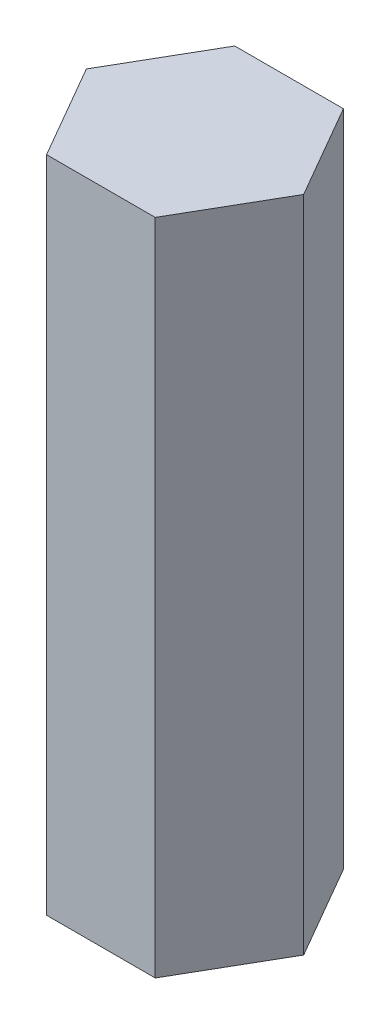
SolidWorks part; units mm, degrees
ref_plane "Plan de face" through (0, 0, 0) normal (0, 0, 1) x (1, 0, 0)
ref_plane "Plan de dessus" through (0, 0, 0) normal (0, 1, 0) x (1, 0, 0)
ref_plane "Plan de droite" through (0, 0, 0) normal (1, 0, 0) x (0, 0, -1)
sketch "Esquisse1" plane through (0, 0, 0) normal (0, 1, 0) x (1, 0, 0)
  line L1 (0, 10) -> (-5.7735, 20)
  line L2 (-5.7735, 20) -> (-17.3205, 20)
  line L3 (-17.3205, 20) -> (-23.094, 10)
  line L4 (-23.094, 10) -> (-17.3205, 0)
  line L5 (-17.3205, 0) -> (-5.7735, 0)
  line L6 (-5.7735, 0) -> (0, 10)
  circle A0 centre (-11.547, 10) radius 10 construction
  point P1 (-144.4106, 41.8031)
  dimension "D2" = 0
  dimension "D1" = 10
  dimension "D3" = 0
extrude "Boss.-Extru.1" add sketch "Esquisse1" along normal blind 70
